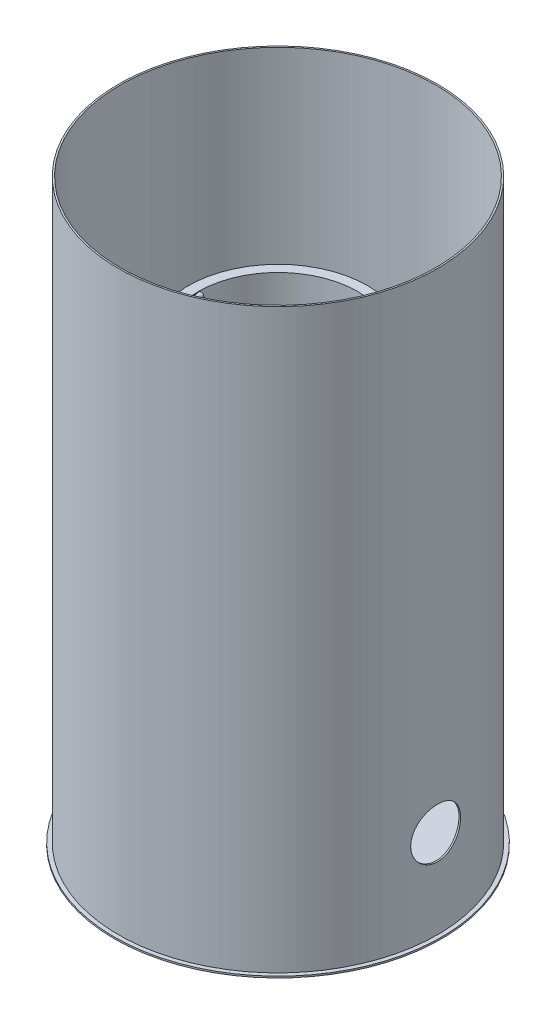
SolidWorks part; units mm, degrees
ref_plane "Front Plane" through (0, 0, 0) normal (0, 0, 1) x (1, 0, 0)
ref_plane "Top Plane" through (0, 0, 0) normal (0, 1, 0) x (1, 0, 0)
ref_plane "Right Plane" through (0, 0, 0) normal (1, 0, 0) x (0, 0, -1)
sketch "Sketch1" plane through (0, 0, 0) normal (0, 0, 1) x (1, 0, 0)
  line L0 (0, -2692.1599) -> (0, 133913.7611) construction
  line L1 (0, 0) -> (104.14, 0)
  line L2 (101.6, 1.016) -> (101.6, 368.3)
  line L3 (57.277, 0) -> (-57.277, 0) construction
  line L4 (0, 0) -> (0, 1.016)
  line L5 (0, 1.016) -> (100.584, 1.016)
  line L6 (100.584, 1.016) -> (100.584, 368.3)
  line L7 (100.584, 368.3) -> (101.6, 368.3)
  line L8 (101.6, 1.016) -> (104.14, 1.016)
  line L9 (104.14, 1.016) -> (104.14, 0)
  line L10 (100.584, 1.016) -> (101.6, 1.016) construction
  dimension "D1" = 203.2
  dimension "D2" = 2.54
  dimension "D3" = 368.3
  dimension "D4" = 1.016
revolve "Revolve1" add sketch "Sketch1" angle 360 about L0
sketch "Sketch2" plane through (0, 0, 0) normal (0, 0, 1) x (1, 0, 0)
  line L0 (114.554, 0) -> (-114.554, 0) construction
  line L3 (57.15, 50.8) -> (57.15, 279.4)
  line L4 (57.15, 279.4) -> (50.8, 279.4)
  line L5 (50.8, 279.4) -> (50.8, 50.8)
  line L6 (57.15, 50.8) -> (50.8, 50.8)
  line L8 (0, -937.2833) -> (0, 49062.7167) construction
  line L9 (50.8, 50.8) -> (57.15, 50.8) construction
  dimension "D1" = 50.8
  dimension "D2" = 6.35
  dimension "D3" = 114.3
  dimension "D5" = 228.6
revolve "Revolve2" add sketch "Sketch2" angle 360 about L8
sketch "Sketch3" plane through (0, 0, 0) normal (0, 0, 1) x (1, 0, 0)
  line L0 (-49.022, 61.087) -> (-49.022, 53.213) construction
  line L1 (-47.244, 61.087) -> (-47.244, 53.213)
  line L2 (-50.8, 61.087) -> (-50.8, 53.213)
  line L3 (-57.15, 50.8) -> (57.15, 50.8) construction
  line L6 (0, -954.5479) -> (0, 49045.4521) construction
  arc A0 (-47.244, 61.087) -> (-50.8, 61.087) centre (-49.022, 61.087) ccw
  arc A1 (-50.8, 53.213) -> (-47.244, 53.213) centre (-49.022, 53.213) ccw
  point P2 (-49.022, 57.15)
  point P7 (-49.022, 62.865)
  point P8 (-49.022, 51.435)
  dimension "D1" = 11.43
  dimension "D2" = 101.6
  dimension "D3" = 3.556
  dimension "D4" = 6.35
sketch "Sketch6" plane through (0, 0, 0) normal (0, 0, 1) x (1, 0, 0)
  line L0 (57.15, 47.1957) -> (57.15, 27.4744)
  line L1 (57.15, 27.4744) -> (0, 27.4744)
  line L2 (57.15, 47.1957) -> (64.4736, 47.1957)
  line L3 (64.4736, 47.1957) -> (64.4736, 21.4063)
  line L4 (64.4736, 21.4063) -> (0, 21.4063)
  line L5 (0, 21.4063) -> (0, 27.4744)
  line L6 (0, -988.3028) -> (0, 49011.6972) construction
  line L7 (57.15, 50.8) -> (57.15, 279.4) construction
revolve "Revolve3" [suppressed] add sketch "Sketch6" angle 360 about L6
ref_plane "Plane1" through (0, 57.15, 0) normal (0, 1, 0) x (1, 0, 0)
sketch "Sketch5" plane through (0, 57.15, 0) normal (0, 1, 0) x (1, 0, 0)
  circle A0 centre (0, 0) radius 49.022
curve "Helix/Spiral1" pitch 24.13 height 217.17 turns 9
sweep "Sweep1" add profiles "Sketch3" path "Helix/Spiral1"
sketch "Sketch7" plane through (0, 0, 0) normal (1, 0, 0) x (0, 0, -1)
  line L0 (0, 114.554) -> (0, -114.554) construction
  line L1 (0, 1.016) -> (0, 368.3) construction
  line L2 (114.554, 0) -> (-114.554, 0) construction
  circle A0 centre (0, 57.15) radius 15.875
  dimension "D1" = 31.75
  dimension "D2" = 57.15
extrude "Cut-Extrude1" cut sketch "Sketch7" along normal through all
